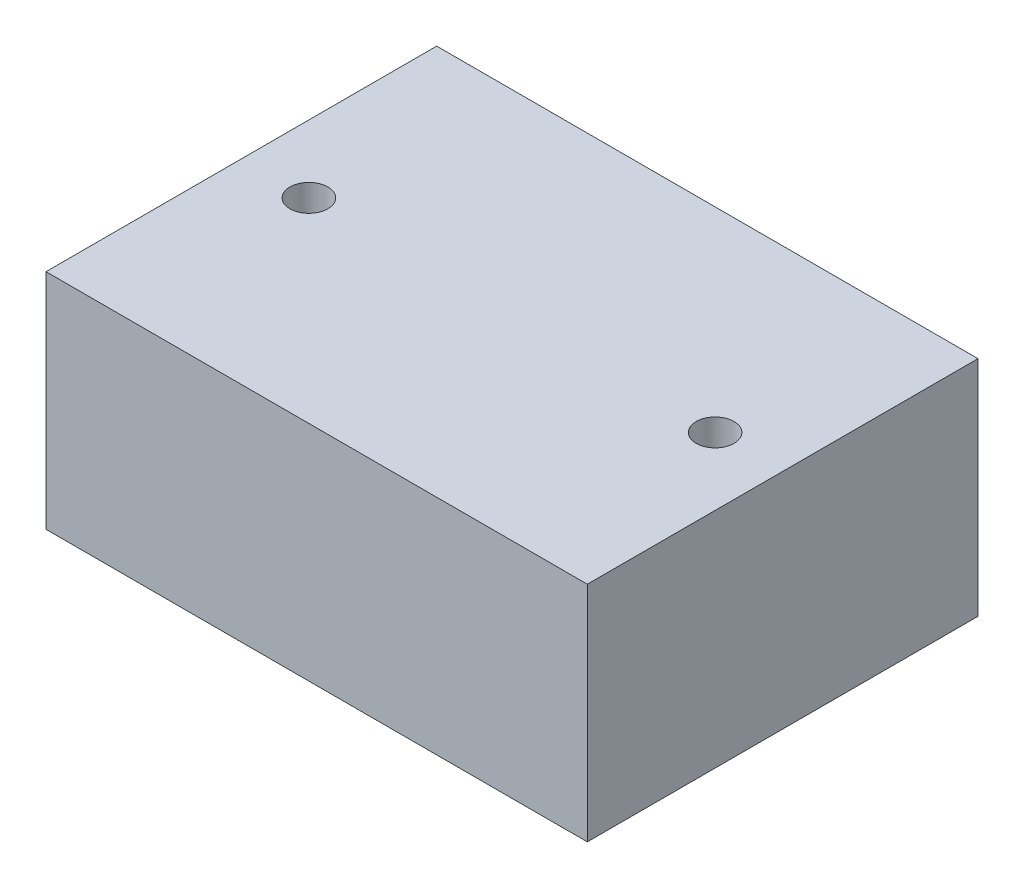
SolidWorks part; units mm, degrees
ref_plane "Front Plane" through (0, 0, 0) normal (0, 0, 1) x (1, 0, 0)
ref_plane "Top Plane" through (0, 0, 0) normal (0, 1, 0) x (1, 0, 0)
ref_plane "Right Plane" through (0, 0, 0) normal (1, 0, 0) x (0, 0, -1)
sketch "Sketch1" plane through (0, 0, 0) normal (0, 1, 0) x (1, 0, 0)
  line L1 (-31.425, -22.68) -> (31.425, -22.68)
  line L2 (-31.425, -22.68) -> (-31.425, 22.68)
  line L3 (-31.425, 22.68) -> (31.425, 22.68)
  line L4 (31.425, -22.68) -> (31.425, 22.68)
  line L5 (-31.425, -22.68) -> (31.425, 22.68) construction
  line L6 (-31.425, 22.68) -> (31.425, -22.68) construction
  point P0 (0, 0)
extrude "Boss-Extrude1" add sketch "Sketch1" along normal blind 25.91
sketch "Sketch2" plane through (0, 0, 0) normal (0, -1, 0) x (1, 0, 0)
  line L0 (31.425, 22.68) -> (31.425, 0) construction
  line L1 (31.425, 22.68) -> (31.425, -22.68) construction
  line L2 (31.425, 0) -> (23.585, 0) construction
  circle A0 centre (23.585, 0) radius 2.2
extrude "Cut-Extrude1" cut sketch "Sketch2" against normal blind 25.91
mirror "Mirror1" about plane through (0, 0, 0) normal (1, 0, 0) of "Cut-Extrude1"
